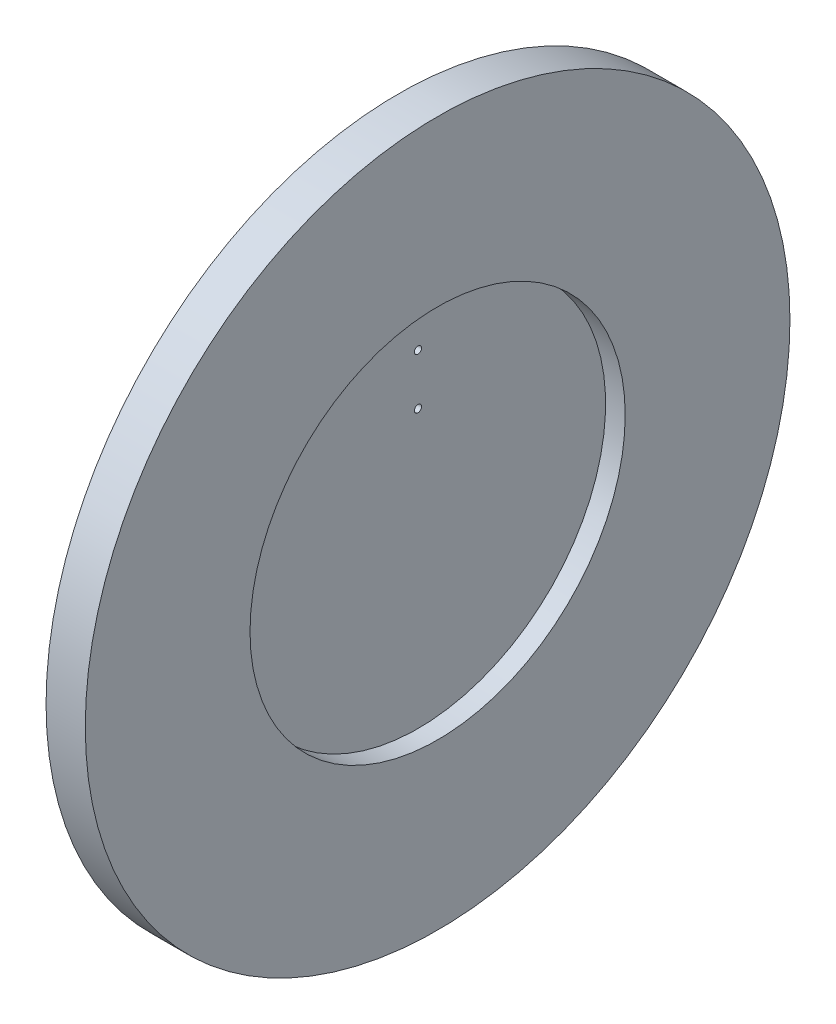
SolidWorks part; units mm, degrees
ref_plane "Front Plane" through (0, 0, 0) normal (0, 0, 1) x (1, 0, 0)
ref_plane "Top Plane" through (0, 0, 0) normal (0, 1, 0) x (1, 0, 0)
ref_plane "Right Plane" through (0, 0, 0) normal (1, 0, 0) x (0, 0, -1)
sketch "Sketch1" plane through (0, 0, 0) normal (1, 0, 0) x (0, 0, -1)
  circle A0 centre (0, 0) radius 89.825
  circle A1 centre (0, 0) radius 47.825
  dimension "D1" = 179.65
  dimension "D2" = 95.65
extrude "Boss-Extrude1" add sketch "Sketch1" along normal blind 10
sketch "Sketch3" plane through (0, 0, 0) normal (-1, 0, 0) x (0, 0, 1)
  circle A0 centre (0, 0) radius 47.825
  dimension "D1" = 95.65
extrude "tbh idk" add sketch "Sketch3" against normal blind 5
sketch "Sketch4" plane through (0, 0, 0) normal (-1, 0, 0) x (0, 0, 1)
  circle A0 centre (0, 0) radius 47.825
  dimension "D1" = 95.65
extrude "Extrusion to Fuel Man" add sketch "Sketch4" along normal blind 5
sketch "Ox Profile" plane through (-5, 0, 0) normal (-1, 0, 0) x (0, 0, 1)
  line L0 (-5.8915, 29.2826) -> (5.8915, 29.2826) construction
  circle A0 centre (0, 29.2826) radius 0.8262 construction
  circle A1 centre (0, 22.8185) radius 0.9146
  circle A2 centre (0, 35.7467) radius 0.9146
  point P11 (0, 29.2826)
  dimension "D1" = 1.6524
  dimension "D3" = 1.8292
  dimension "D2" = 29.2826
  dimension "D4" = 6.4641
extrude "Ox Downcomer" cut sketch "Ox Profile" against normal up to next
equation "\"Flange_Dia\"= 179.65"
equation "\"Regen_Thickness\"= 1.5"
equation "\"Regen_To_Inner\"=2"
equation "\"Faceplate_Area\"=95.65"
equation "\"Regen_Rib_Thickness\"=1"
equation "\"Flange_Thickness\"= 10"
equation "\"Faceplate_To_Chamber_Extrusion\"=1"
equation "\"Injector_MCCN_O-Ring\"=3"
equation "\"Ox_Orifice\" = 1.829247371"
equation "\"Fuel_Orifice\"= 1.65242067"
equation "\"OxFuel_Dist_Downstream\"= 3"
equation "\"Fuel_Dist_From_Center\"=29.2826"
equation "\"OxFuel_HalfAngle\"=30"
equation "\"D1@Sketch1\"=\"Flange_Dia\""
equation "\"D2@Sketch1\"=\"Faceplate_Area\""
equation "\"D1@Boss-Extrude1\"=\"Flange_Thickness\""
equation "\"D1@Sketch3\"=\"Faceplate_Area\""
equation "\"D1@tbh idk\" = \"Flange_Thickness\" / 2"
equation "\"D1@Sketch4\"=\"Faceplate_Area\""
equation "\"D1@Extrusion to Fuel Man\" = \"Flange_Thickness\" / 2"
equation "\"D1@Ox Profile\" = \"Fuel_Orifice\""
equation "\"D2@Ox Profile\" = \"Fuel_Dist_From_Center\""
equation "\"D3@Ox Profile\" = \"Ox_Orifice\""
equation "\"D1@Flange\" = \"Flange_Thickness\""
equation "\"D1@Regen Slots Sketch\" = \"Regen_Rib_Thickness\""
equation "\"D2@Regen Slots Sketch\" = \"Regen_Thickness\""
equation "\"D3@Regen Slots Sketch\" = \"Regen_To_Inner\""
equation "\"D1@Faceplate Extrusion to Manifold Sketch\" = \"Faceplate_Area\""
equation "\"D1@Faceplate Extrusion to Chamber Sketch\" = \"Faceplate_Area\""
equation "\"D1@Faceplate Extrusion to Chamber\"=\"Faceplate_To_Chamber_Extrusion\""
equation "\"D1@O-Ring Slot Sketch\" = \"Faceplate_Area\""
equation "\"D2@O-Ring Slot Sketch\" = \"Injector_MCCN_O-Ring\""
equation "\"D1@O-Ring Slot\" =  ( \"Faceplate_To_Chamber_Extrusion\" )  +  ( \"Injector_MCCN_O-Ring\" / 2 ) "
equation "\"D1@Fuel Orifices Sketch\" = \"Ox_Orifice\""
equation "\"D2@Fuel Orifices Sketch\" = \"Fuel_Orifice\""
equation "\"D5@Fuel Orifices Sketch\" = \"Fuel_Dist_From_Center\""
equation "\"D3@Fuel Orifices Sketch\" = \"OxFuel_Dist_Downstream\""
equation "\"D4@Fuel Orifices Sketch\" = \"OxFuel_Dist_Downstream\""
equation "\"D1@Ox1 Profile\" = \"Ox_Orifice\""
equation "\"D1@Ox2 Profile\" = \"Ox_Orifice\""
equation "\"D1@Ox2 Guide Curve\" = \"OxFuel_HalfAngle\""
equation "\"D2@Ox1 Profile\" = \"OxFuel_Dist_Downstream\""
equation "\"D2@Ox2 Profile\"=\"OxFuel_Dist_Downstream\""
equation "\"D1@Ox1 Guide Curve\"=\"OxFuel_HalfAngle\""
equation "\"Thickness_FuelMan\"=5"
equation "\"D1@Faceplate Extrusion to Manifold\"=\"Thickness_FuelMan\""
equation "\"OxFuel_Dist_Upstream\"=(((\"Thickness_FuelMan\" + \"Faceplate_To_Chamber_Extrusion\")*tan(\"OxFuel_HalfAngle\")))+(\"OxFuel_Dist_Downstream\")"
equation "\"D4@Ox Profile\"=\"OxFuel_Dist_Upstream\""
